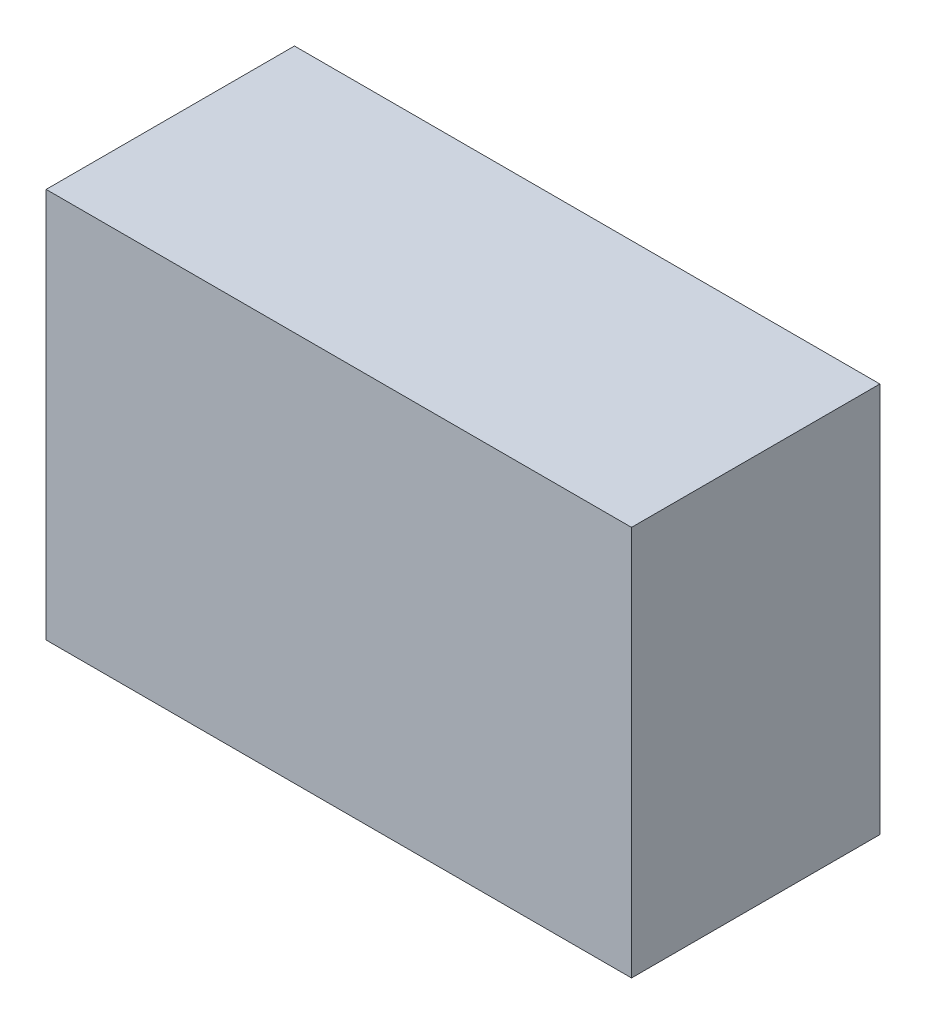
SolidWorks part; units mm, degrees
ref_plane "Front Plane" through (0, 0, 0) normal (0, 0, 1) x (1, 0, 0)
ref_plane "Top Plane" through (0, 0, 0) normal (0, 1, 0) x (1, 0, 0)
ref_plane "Right Plane" through (0, 0, 0) normal (1, 0, 0) x (0, 0, -1)
sketch "Sketch1" plane through (0, 0, 0) normal (0, 0, 1) x (1, 0, 0)
  line L1 (0, 0) -> (8.25, 0)
  line L2 (0, 0) -> (0, 5.5)
  line L3 (0, 5.5) -> (8.25, 5.5)
  line L4 (8.25, 0) -> (8.25, 5.5)
  dimension "D1" = 5.5
  dimension "D2" = 8.25
extrude "Boss-Extrude1" add sketch "Sketch1" along normal blind 3.5
